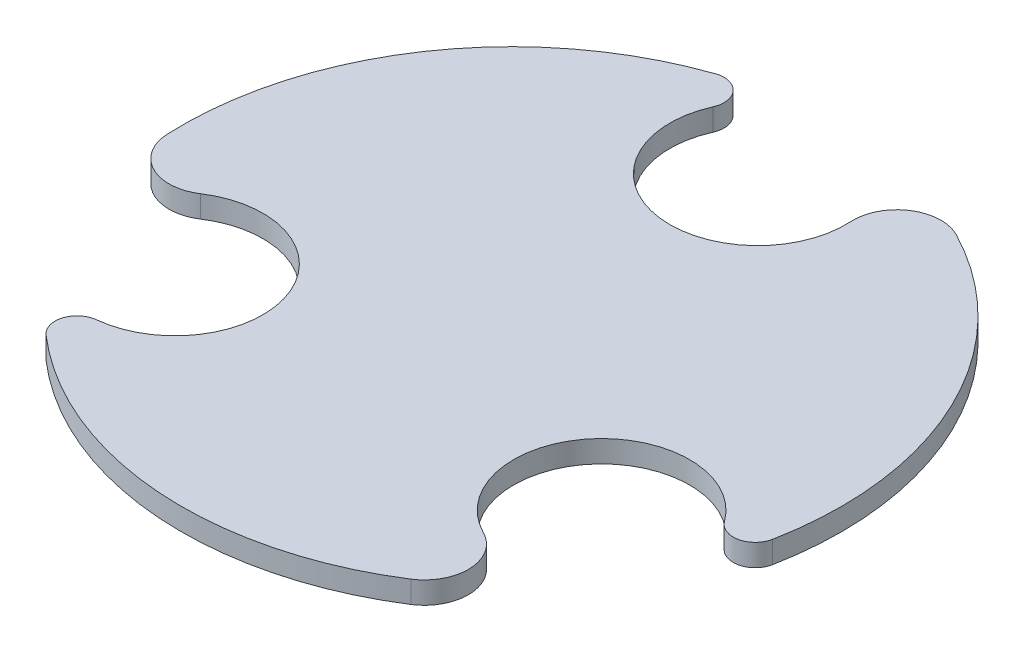
SolidWorks part; units mm, degrees
ref_plane "Front Plane" through (0, 0, 0) normal (0, 0, 1) x (1, 0, 0)
ref_plane "Top Plane" through (0, 0, 0) normal (0, 1, 0) x (1, 0, 0)
ref_plane "Right Plane" through (0, 0, 0) normal (1, 0, 0) x (0, 0, -1)
sketch "Sketch2" plane through (0, 0, 0) normal (0, 1, 0) x (1, 0, 0)
  circle A3 centre (0, 0) radius 75
  dimension "D1" = 150
extrude "Boss-Extrude2" add sketch "Sketch2" along normal blind 5
sketch "Sketch3" plane through (0, 5, 0) normal (0, 1, 0) x (1, 0, 0)
  circle A0 centre (0, 56) radius 20
  circle A2 centre (48.4974, -28) radius 20
  circle A3 centre (-48.4974, -28) radius 20
  point P3 (-48.6211, -12.8365)
  point P5 (0, 0)
  point P6 (-37.4005, -42.9291)
  point P7 (0, 0)
  point P11 (0, 0)
  point P13 (0, 0)
  dimension "D1" = 40
  dimension "D3" = 56
  dimension "D2" = 3
extrude "Cut-Extrude2" cut sketch "Sketch3" against normal through all
fillet "Fillet2" radius 10 3 edges at (61.0409, 2.5, 43.5775) (7.2188, 2.5, -74.6518) (-68.2597, 2.5, 31.0742)
fillet "Fillet3" radius 5 3 edges at (-7.2188, 2.5, -74.6518) (-61.0409, 2.5, 43.5775) (68.2597, 2.5, 31.0742)
